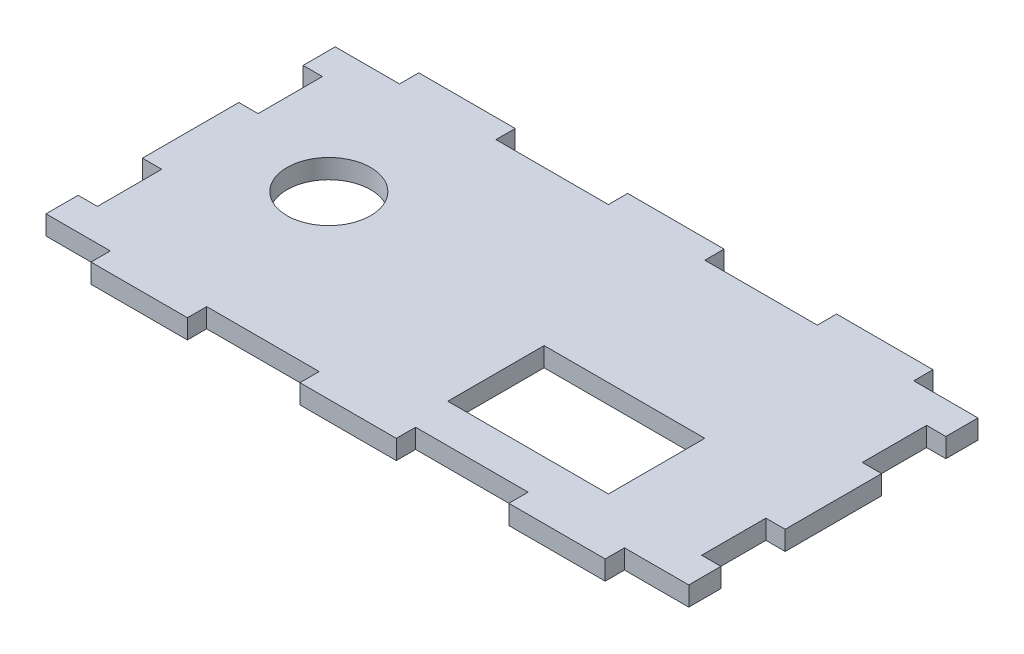
SolidWorks part; units mm, degrees
ref_plane "前视基准面" through (0, 0, 0) normal (0, 0, 1) x (1, 0, 0)
ref_plane "上视基准面" through (0, 0, 0) normal (0, 1, 0) x (1, 0, 0)
ref_plane "右视基准面" through (0, 0, 0) normal (1, 0, 0) x (0, 0, -1)
sketch "草图1" plane through (0, 0, 0) normal (0, 1, 0) x (1, 0, 0)
  line L0 (0, -22.5) -> (0, 22.5) construction
  line L1 (-50, -22.5) -> (-40, -22.5)
  line L2 (-50, -22.5) -> (-50, -17.5)
  line L3 (-50, 22.5) -> (-40, 22.5)
  line L4 (50, -22.5) -> (50, -17.5)
  line L5 (-50, -22.5) -> (50, 22.5) construction
  line L6 (-50, 22.5) -> (50, -22.5) construction
  line L7 (-50, 17.5) -> (-47, 17.5)
  line L8 (-50, -7.5) -> (-50, 7.5)
  line L9 (-50, 7.5) -> (-47, 7.5)
  line L10 (-47, 17.5) -> (-47, 7.5)
  line L11 (-50, 0) -> (50, 0) construction
  line L12 (-50, -7.5) -> (-47, -7.5)
  line L13 (-50, -17.5) -> (-47, -17.5)
  line L14 (-47, -17.5) -> (-47, -7.5)
  line L15 (-50, 17.5) -> (-50, 22.5)
  line L16 (50, -17.5) -> (47, -17.5)
  line L17 (47, -17.5) -> (47, -7.5)
  line L18 (50, -7.5) -> (47, -7.5)
  line L19 (50, 7.5) -> (47, 7.5)
  line L20 (47, 17.5) -> (47, 7.5)
  line L21 (50, 17.5) -> (47, 17.5)
  line L22 (50, 17.5) -> (50, 22.5)
  line L23 (50, -7.5) -> (50, 7.5)
  line L24 (-25, 22.5) -> (-7.5, 22.5)
  line L25 (7.5, 22.5) -> (25, 22.5)
  line L26 (-40, 22.5) -> (-40, 25.5)
  line L27 (-40, 25.5) -> (-25, 25.5)
  line L28 (-25, 22.5) -> (-25, 25.5)
  line L29 (40, 22.5) -> (40, 25.5)
  line L30 (-7.5, 22.5) -> (-7.5, 25.5)
  line L31 (-7.5, 25.5) -> (7.5, 25.5)
  line L32 (7.5, 22.5) -> (7.5, 25.5)
  line L33 (25, 22.5) -> (25, 25.5)
  line L34 (40, 25.5) -> (25, 25.5)
  line L35 (40, 22.5) -> (50, 22.5)
  line L36 (40, -22.5) -> (40, -25.5)
  line L37 (40, -25.5) -> (25, -25.5)
  line L38 (25, -22.5) -> (25, -25.5)
  line L39 (7.5, -22.5) -> (7.5, -25.5)
  line L40 (-7.5, -25.5) -> (7.5, -25.5)
  line L41 (-7.5, -22.5) -> (-7.5, -25.5)
  line L42 (-25, -22.5) -> (-25, -25.5)
  line L43 (-40, -25.5) -> (-25, -25.5)
  line L44 (-40, -22.5) -> (-40, -25.5)
  line L45 (-25, -22.5) -> (-7.5, -22.5)
  line L46 (7.5, -22.5) -> (25, -22.5)
  line L47 (40, -22.5) -> (50, -22.5)
  point P0 (0, 0)
  point P13 (0, 0)
  point P16 (0, 0)
  point P36 (0, 25.5)
  dimension "D1" = 45
  dimension "D2" = 100
  dimension "D3" = 3
  dimension "D4" = 10
  dimension "D5" = 5
  dimension "D6" = 15
  dimension "D7" = 3
  dimension "D8" = 15
  dimension "D9" = 3
  dimension "D10" = 10
extrude "凸台-拉伸1" add sketch "草图1" along normal blind 3
sketch "草图2" plane through (0, 3, 0) normal (0, 1, 0) x (1, 0, 0)
  line L1 (50, -7.5) -> (50, 7.5) construction
  line L2 (6.5, -1.5) -> (31.5, -1.5)
  line L3 (6.5, -1.5) -> (6.5, -16.5)
  line L4 (6.5, -16.5) -> (31.5, -16.5)
  line L7 (31.5, -1.5) -> (31.5, -16.5)
  line L8 (6.5, -1.5) -> (31.5, -16.5) construction
  line L9 (6.5, -16.5) -> (31.5, -1.5) construction
  line L10 (7.5, -22.5) -> (25, -22.5) construction
  line L11 (-25, -22.5) -> (-7.5, -22.5) construction
  line L12 (-50, 7.5) -> (-50, -7.5) construction
  circle A0 centre (-31, 2.5) radius 6.5
  point P0 (19, -9)
  dimension "D5" = 25
  dimension "D6" = 13
  dimension "D7" = 19
  dimension "D1" = 18.5
  dimension "D2" = 6
  dimension "D3" = 25
  dimension "D4" = 15
extrude "切除-拉伸1" cut sketch "草图2" against normal through all
